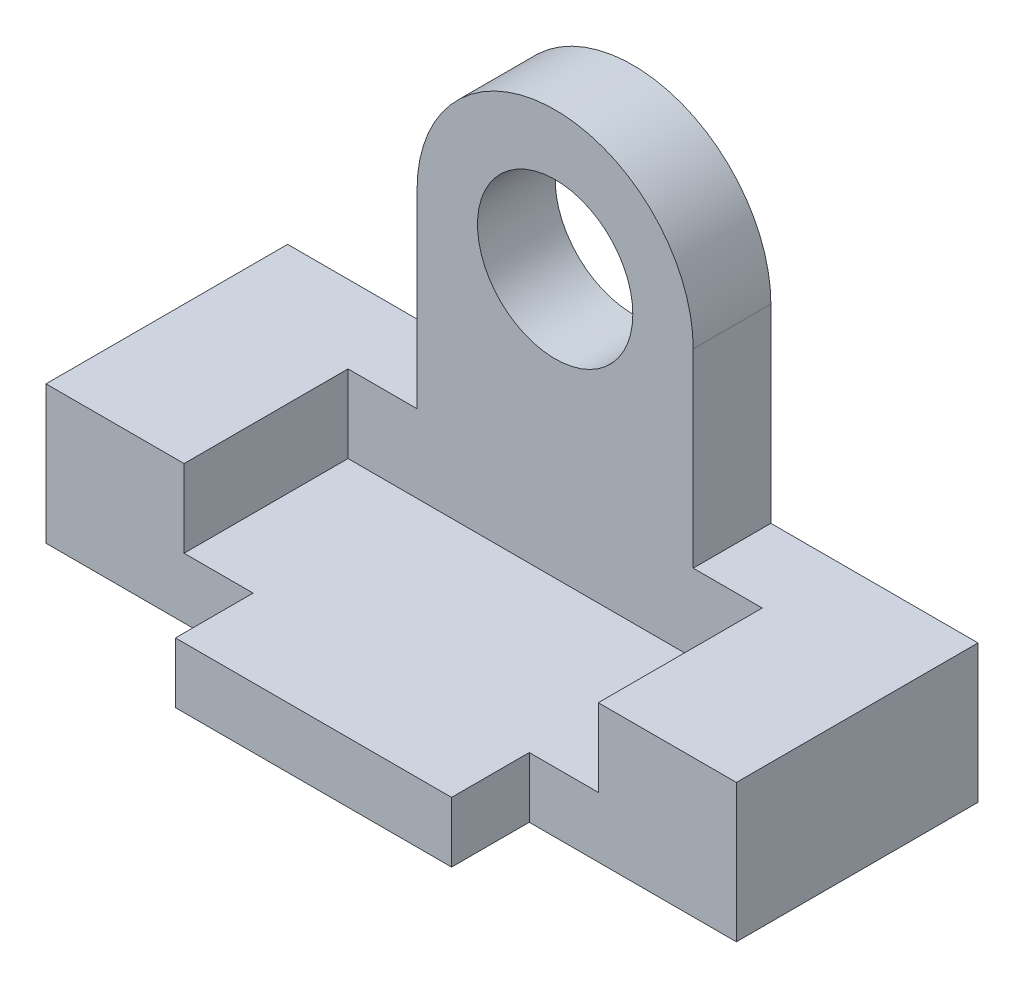
SolidWorks part; units mm, degrees
ref_plane "前视基准面" through (0, 0, 0) normal (0, 0, 1) x (1, 0, 0)
ref_plane "上视基准面" through (0, 0, 0) normal (0, 1, 0) x (1, 0, 0)
ref_plane "右视基准面" through (0, 0, 0) normal (1, 0, 0) x (0, 0, -1)
other "Configuration Table"
sketch "草图1" plane through (0, 0, 0) normal (0, 1, 0) x (1, 0, 0)
  line L1 (-40, -14) -> (40, -14)
  line L2 (-40, -14) -> (-40, 14)
  line L3 (-40, 14) -> (40, 14)
  line L4 (40, -14) -> (40, 14)
  line L5 (-40, -14) -> (40, 14) construction
  line L6 (-40, 14) -> (40, -14) construction
  point P0 (0, 0)
  dimension "D1" = 28
  dimension "D2" = 80
extrude "凸台-拉伸1" add sketch "草图1" along normal blind 16
sketch "草图2" plane through (0, 16, 0) normal (0, 1, 0) x (1, 0, 0)
  line L0 (0, -1000) -> (0, 49000) construction
  line L1 (-40, -14) -> (40, -14) construction
  line L2 (-24, -14) -> (24, -14)
  line L3 (-24, -14) -> (-24, 5)
  line L4 (-24, 5) -> (24, 5)
  line L5 (24, -14) -> (24, 5)
  dimension "D1" = 48
  dimension "D2" = 19
extrude "切除-拉伸1" cut sketch "草图2" against normal blind 9
sketch "草图3" plane through (0, 0, 14) normal (0, 0, 1) x (1, 0, 0)
  line L0 (-40, 0) -> (40, 0) construction
  line L1 (-16, 0) -> (16, 0)
  line L2 (-16, 0) -> (-16, 7)
  line L3 (-16, 7) -> (16, 7)
  line L4 (16, 0) -> (16, 7)
  line L5 (-24, 7) -> (24, 7) construction
  line L6 (0, -1000) -> (0, 49000) construction
  dimension "D1" = 32
extrude "凸台-拉伸2" add sketch "草图3" along normal blind 9
sketch "草图4" plane through (0, 0, -5) normal (0, 0, 1) x (1, 0, 0)
  line L0 (0, -1000) -> (0, 49000) construction
  line L1 (24, 16) -> (-24, 16) construction
  line L2 (-16, 16) -> (16, 16)
  line L3 (-16, 16) -> (-16, 38)
  line L4 (-16, 38) -> (16, 38) construction
  line L5 (16, 16) -> (16, 38)
  line L6 (16, 0) -> (40, 0) construction
  arc A0 (16, 38) -> (-16, 38) centre (0, 38) ccw
  circle A1 centre (0, 38) radius 9
  dimension "D1" = 16
  dimension "D2" = 18
  dimension "D3" = 38
extrude "凸台-拉伸3" add sketch "草图4" against normal up to surface (9 mm away) up to face at (0, 8, -14)
